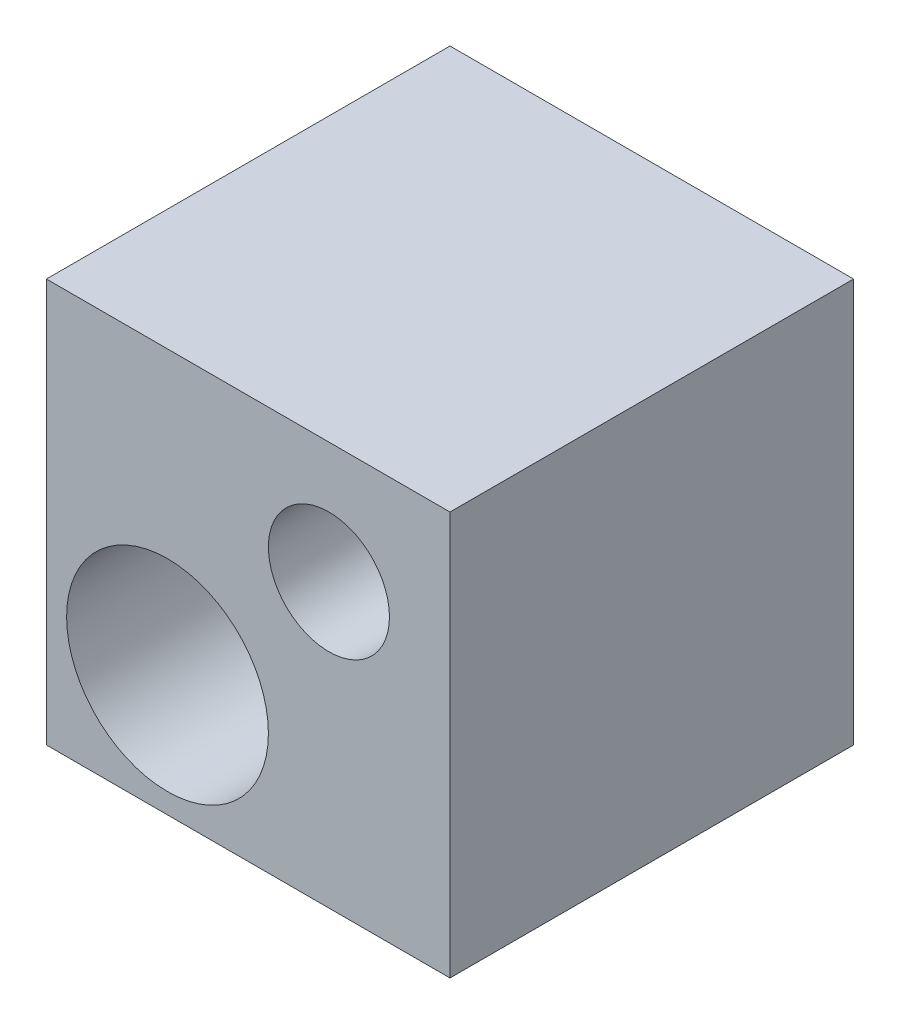
SolidWorks part; units mm, degrees
ref_plane "Front Plane" through (0, 0, 0) normal (0, 0, 1) x (1, 0, 0)
ref_plane "Top Plane" through (0, 0, 0) normal (0, 1, 0) x (1, 0, 0)
ref_plane "Right Plane" through (0, 0, 0) normal (1, 0, 0) x (0, 0, -1)
sketch "Sketch1" plane through (0, 0, 0) normal (0, 0, 1) x (1, 0, 0)
  line L1 (0, 0) -> (10, 0)
  line L2 (0, 0) -> (0, 10)
  line L3 (0, 10) -> (10, 10)
  line L4 (10, 0) -> (10, 10)
extrude "Boss-Extrude1" add sketch "Sketch1" along normal blind 10
sketch "Sketch2" plane through (0, 0, 0) normal (0, 0, 1) x (1, 0, 0)
  circle A0 centre (3, 3) radius 2.5
  circle A1 centre (7, 7) radius 1.5
extrude "Cut-Extrude2" cut sketch "Sketch2" along normal through all
